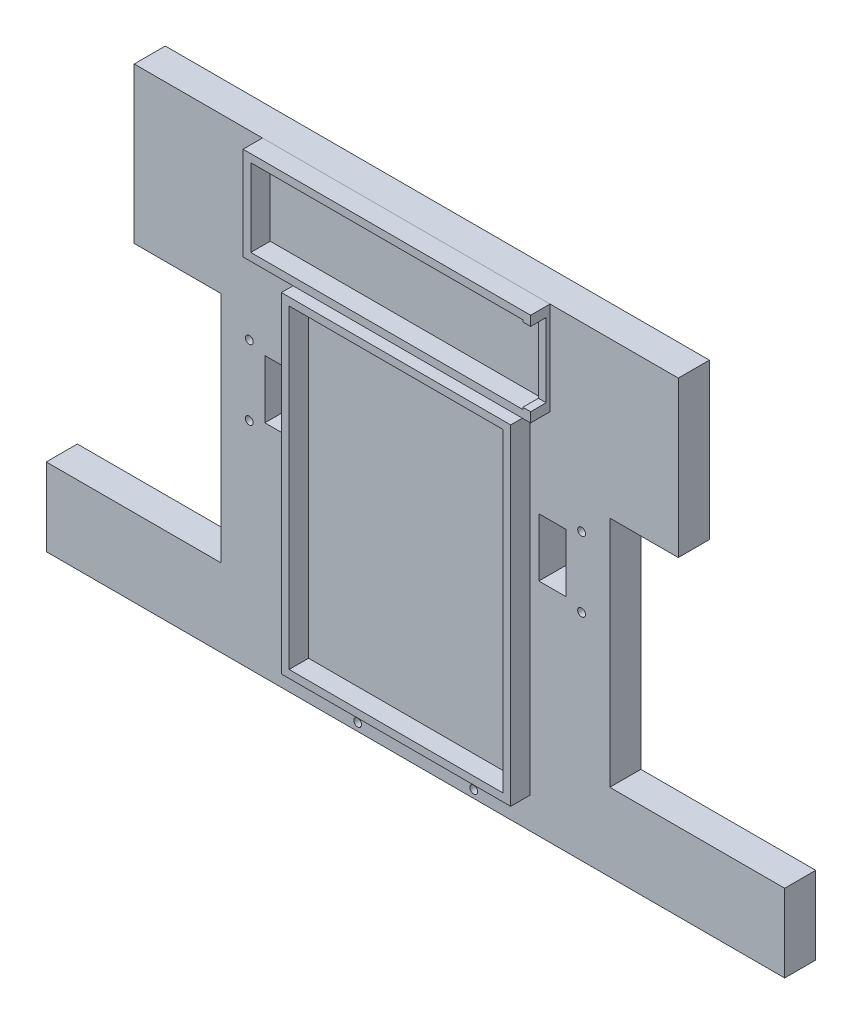
SolidWorks part; units mm, degrees
ref_plane "Plano frontal" through (0, 0, 0) normal (0, 0, 1) x (1, 0, 0)
ref_plane "Plano superior" through (0, 0, 0) normal (0, 1, 0) x (1, 0, 0)
ref_plane "Plano direito" through (0, 0, 0) normal (1, 0, 0) x (0, 0, -1)
sketch "Esboço1" plane through (0, 0, 0) normal (0, 0, 1) x (1, 0, 0)
  line L1 (39.4082, 102.513) -> (39.4082, 62.513)
  line L2 (39.4082, 62.513) -> (21.778, 62.513)
  line L3 (21.778, 62.513) -> (21.778, 2.513)
  line L4 (21.778, 2.513) -> (66.778, 2.513)
  line L5 (66.778, 2.513) -> (66.778, -17.487)
  line L6 (66.778, -17.487) -> (-123.222, -17.487)
  line L7 (-123.222, -17.487) -> (-123.222, 2.513)
  line L8 (-123.222, 2.513) -> (-78.222, 2.513)
  line L9 (-78.222, 2.513) -> (-78.222, 62.513)
  line L10 (-78.222, 62.513) -> (-100.5918, 62.513)
  line L11 (-100.5918, 62.513) -> (-100.5918, 102.513)
  line L13 (-100.5918, 102.513) -> (39.4082, 102.513)
  dimension "D1" = 140
  dimension "D2" = 190
  dimension "D4" = 100
  dimension "D5" = 45
  dimension "D6" = 60
  dimension "D7" = 60
  dimension "D8" = 40
  dimension "D9" = 40
  dimension "D10" = 20
extrude "Ressalto-extrusão1" add sketch "Esboço1" along normal blind 8
sketch "Esboço2" plane through (0, 0, 8) normal (0, 0, 1) x (1, 0, 0)
  line L0 (21.778, 2.513) -> (21.778, 62.513) construction
  line L1 (-55.722, 73.513) -> (-0.722, 73.513)
  line L2 (-55.722, 73.513) -> (-55.722, -7.487)
  line L3 (-55.722, -7.487) -> (-0.722, -7.487)
  line L4 (-0.722, 73.513) -> (-0.722, -7.487)
  line L5 (-123.222, -17.487) -> (66.778, -17.487) construction
  line L9 (-57.722, 75.513) -> (1.278, 75.513)
  line L10 (-57.722, 75.513) -> (-57.722, -9.487)
  line L11 (-57.722, -9.487) -> (1.278, -9.487)
  line L12 (1.278, 75.513) -> (1.278, -9.487)
  dimension "D1" = 55
  dimension "D2" = 81
  dimension "D3" = 22.5
  dimension "D4" = 10
  dimension "D5" = 2
  dimension "D6" = 2
  dimension "D7" = 2
  dimension "D8" = 2
extrude "Ressalto-extrusão2" add sketch "Esboço2" along normal blind 5
sketch "Esboço3" plane through (0, 0, 8) normal (0, 0, 1) x (1, 0, 0)
  line L0 (-28.222, -9.487) -> (-28.222, -17.487)
  line L1 (-57.722, -9.487) -> (1.278, -9.487) construction
  line L2 (-123.222, -17.487) -> (66.778, -17.487) construction
  line L3 (-28.222, -17.487) -> (-13.222, -17.487)
  line L4 (-28.222, -17.487) -> (-43.222, -17.487)
  circle A0 centre (-43.1, -15.487) radius 1
  circle A1 centre (-13.222, -15.487) radius 1
  dimension "D3" = 2
  dimension "D5" = 2
  dimension "D1" = 15
  dimension "D2" = 15
  dimension "D4" = 2
  dimension "D6" = 2
extrude "Corte-extrusão1" cut sketch "Esboço3" against normal through all contours A1 | A0
sketch "Esboço4" plane through (0, 0, 8) normal (0, 0, 1) x (1, 0, 0)
sketch "Esboço5" plane through (0, 0, 8) normal (0, 0, 1) x (1, 0, 0)
  line L0 (-100.5918, 102.513) -> (-100.5918, 62.513) construction
  line L1 (-65.5918, 100.5163) -> (4.4082, 100.5163)
  line L2 (-65.5918, 100.5163) -> (-65.5918, 80.5163)
  line L3 (-65.5918, 80.5163) -> (4.4082, 80.5163)
  line L4 (4.4082, 100.5163) -> (4.4082, 80.5163)
  line L7 (-67.5918, 102.5163) -> (6.4082, 102.5163)
  line L8 (-67.5918, 102.5163) -> (-67.5918, 78.5163)
  line L9 (-67.5918, 78.5163) -> (6.4082, 78.5163)
  line L10 (6.4082, 102.5163) -> (6.4082, 78.5163)
  dimension "D1" = 20
  dimension "D2" = 70
  dimension "D3" = 35
  dimension "D4" = 2
  dimension "D5" = 2
  dimension "D6" = 2
  dimension "D7" = 2
extrude "Ressalto-extrusão4" add sketch "Esboço5" along normal blind 5
sketch "Esboço6" plane through (0, 0, 13) normal (0, 0, 1) x (1, 0, 0)
  line L0 (4.4082, 80.5163) -> (4.4082, 100.5163) construction
  line L1 (4.4082, 100.0163) -> (6.4082, 100.0163)
  line L2 (4.4082, 100.0163) -> (4.4082, 81.0163)
  line L3 (4.4082, 81.0163) -> (6.4082, 81.0163)
  line L4 (6.4082, 100.0163) -> (6.4082, 81.0163)
  line L5 (6.4082, 78.5163) -> (6.4082, 102.5163) construction
  line L6 (6.4082, 102.5163) -> (-67.5918, 102.5163) construction
  line L7 (-67.5918, 78.5163) -> (6.4082, 78.5163) construction
  dimension "D1" = 2.5
  dimension "D2" = 2.5
extrude "Corte-extrusão2" cut sketch "Esboço6" against normal blind 4 contours L2 L1 L4 L3
sketch "Esboço7" plane through (0, 0, 8) normal (0, 0, 1) x (1, 0, 0)
  line L0 (-78.222, 32.513) -> (-78.222, 41.513)
  line L1 (-78.222, 62.513) -> (-78.222, 2.513) construction
  line L2 (-78.222, 32.513) -> (-78.222, 23.513)
  line L3 (39.4082, 102.513) -> (6.4082, 102.513) construction
  line L5 (21.778, 2.513) -> (21.778, 62.513) construction
  line L7 (-66.972, 54.3514) -> (-59.972, 54.3514)
  line L8 (-66.972, 54.3514) -> (-66.972, 39.3514)
  line L9 (-66.972, 39.3514) -> (-59.972, 39.3514)
  line L10 (-59.972, 54.3514) -> (-59.972, 39.3514)
  line L11 (3.528, 54.3514) -> (10.528, 54.3514)
  line L12 (3.528, 54.3514) -> (3.528, 39.3514)
  line L13 (3.528, 39.3514) -> (10.528, 39.3514)
  line L14 (10.528, 54.3514) -> (10.528, 39.3514)
  circle A0 centre (14.528, 55.8514) radius 1
  circle A2 centre (-70.972, 55.8514) radius 1
  circle A3 centre (-70.972, 37.8514) radius 1
  circle A4 centre (14.528, 37.8514) radius 1
  point P27 (0, 0)
  dimension "D3" = 2
  dimension "D6" = 2
  dimension "D8" = 7.25
  dimension "D11" = 7.25
  dimension "D12" = 7.25
  dimension "D13" = 2
  dimension "D14" = 2
  dimension "D4" = 46.6617
  dimension "D1" = 9
  dimension "D2" = 9
  dimension "D5" = 18
  dimension "D7" = 7.25
  dimension "D15" = 15
  dimension "D16" = 7
  dimension "D17" = 4
  dimension "D18" = 7
  dimension "D19" = 15
  dimension "D20" = 4
extrude "Corte-extrusão4" cut sketch "Esboço7" against normal through all
